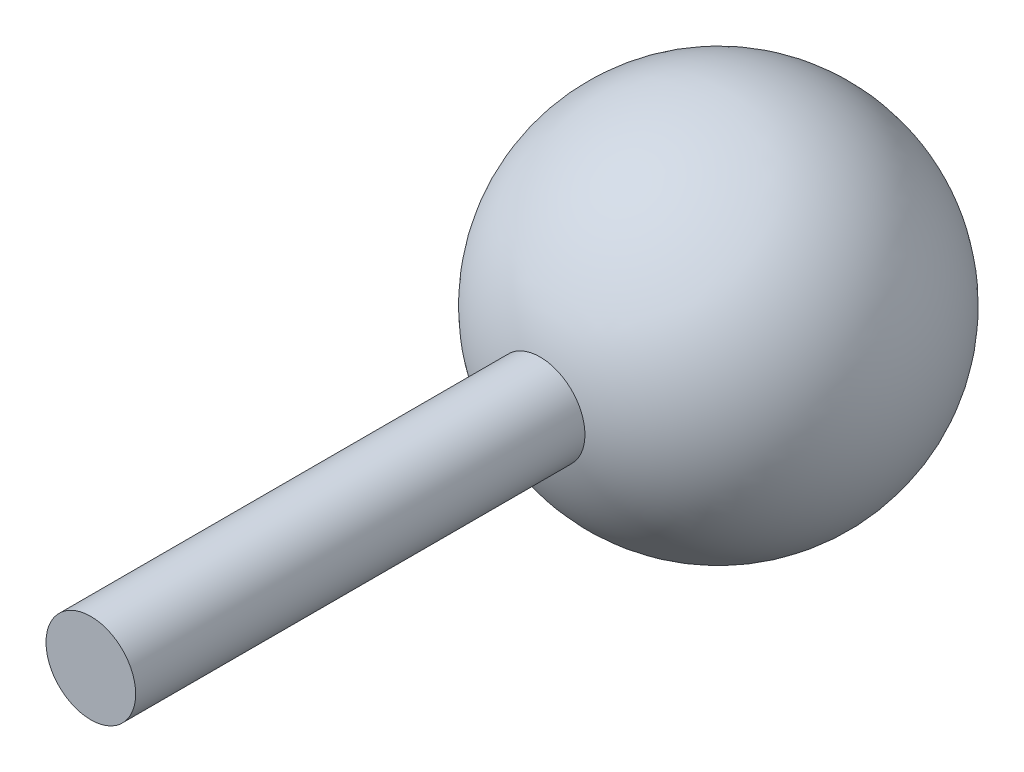
SolidWorks part; units mm, degrees
ref_plane "Front Plane" through (0, 0, 0) normal (0, 0, 1) x (1, 0, 0)
ref_plane "Top Plane" through (0, 0, 0) normal (0, 1, 0) x (1, 0, 0)
ref_plane "Right Plane" through (0, 0, 0) normal (1, 0, 0) x (0, 0, -1)
sketch "Sketch2" plane through (0, 0, 0) normal (0, 0, 1) x (1, 0, 0)
  line L0 (0, 41) -> (0, -41)
  line L1 (0, 90.0699) -> (0, -90.0699) construction
  arc A0 (0, 41) -> (0, -41) centre (0, 0) ccw
  point P8 (0, 0)
  dimension "D2" = 41
revolve "Revolve5" add sketch "Sketch2" angle 360 about L1
sketch "Sketch4" plane through (0, 0, 0) normal (0, 0, 1) x (1, 0, 0)
  circle A0 centre (0, 0) radius 10
  dimension "D1" = 20
extrude "Boss-Extrude1" add sketch "Sketch4" along normal blind 140
